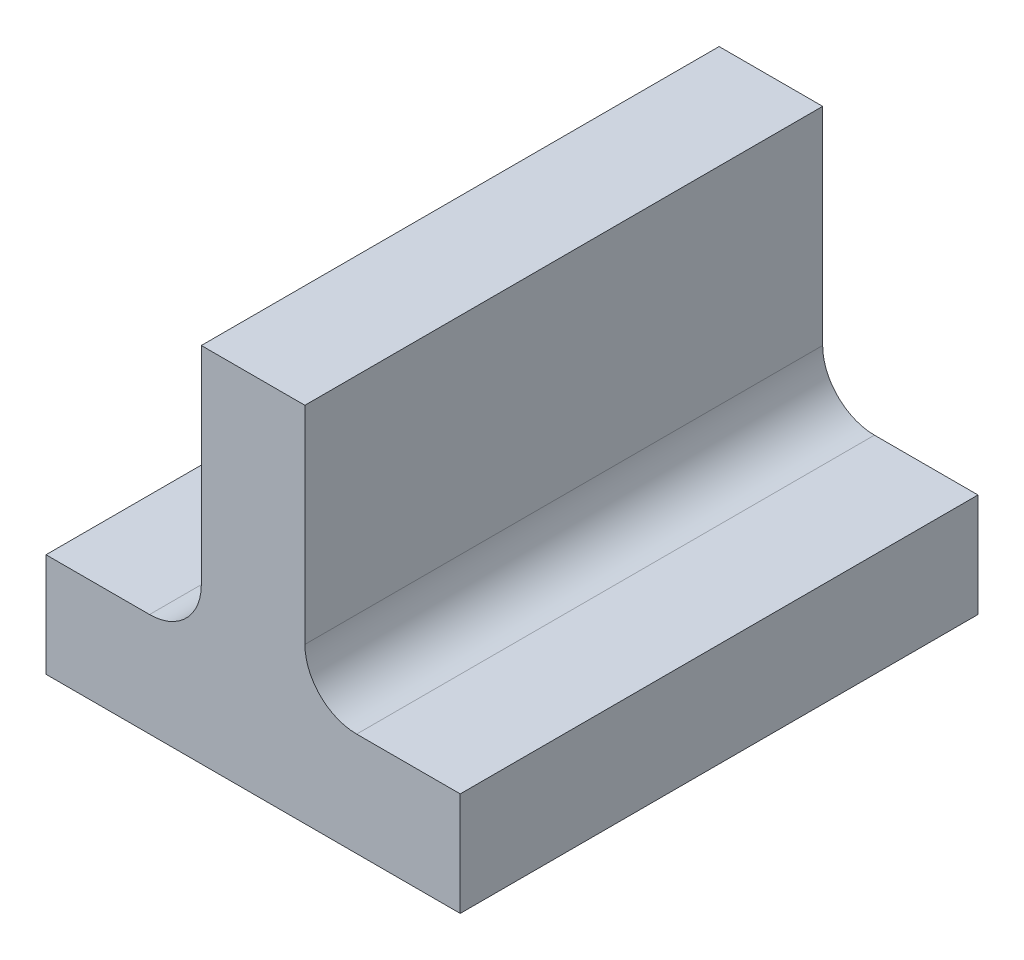
SolidWorks part; units mm, degrees
ref_plane "Plan de face" through (0, 0, 0) normal (0, 0, 1) x (1, 0, 0)
ref_plane "Plan de dessus" through (0, 0, 0) normal (0, 1, 0) x (1, 0, 0)
ref_plane "Plan de droite" through (0, 0, 0) normal (1, 0, 0) x (0, 0, -1)
sketch "Esquisse1" plane through (0, 0, 0) normal (0, 0, 1) x (1, 0, 0)
  line L0 (-8, 0) -> (8, 0)
  line L1 (8, 0) -> (8, 4)
  line L2 (8, 4) -> (2, 4)
  line L3 (2, 4) -> (2, 14)
  line L4 (2, 14) -> (-2, 14)
  line L5 (-2, 14) -> (-2, 4)
  line L6 (-2, 4) -> (-8, 4)
  line L7 (-8, 4) -> (-8, 0)
  dimension "D1" = 16
  dimension "D2" = 8
  dimension "D3" = 14
  dimension "D4" = 4
  dimension "D5" = 4
  dimension "D6" = 6
  dimension "D7" = 4
extrude "Boss.-Extru.1" add sketch "Esquisse1" along normal blind 20
fillet "Congé1" radius 2 2 edges at (2, 4, 10) (-2, 4, 10)
